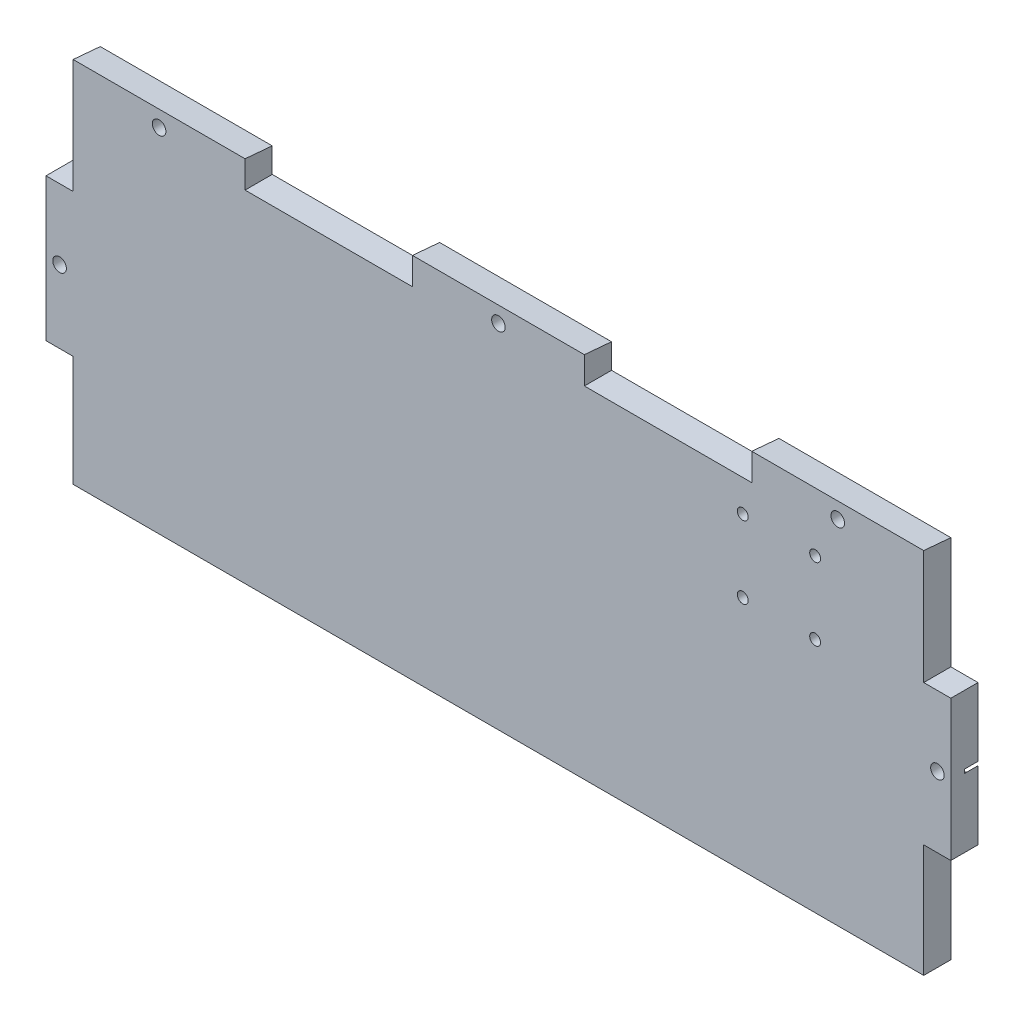
SolidWorks part; units mm, degrees
ref_plane "Plan de face" through (0, 0, 0) normal (0, 0, 1) x (1, 0, 0)
ref_plane "Plan de dessus" through (0, 0, 0) normal (0, 1, 0) x (1, 0, 0)
ref_plane "Plan de droite" through (0, 0, 0) normal (1, 0, 0) x (0, 0, -1)
sketch "Esquisse1" plane through (0, 0, 0) normal (0, 0, 1) x (1, 0, 0)
  line L1 (0, 0) -> (-188, 0)
  line L2 (0, 0) -> (0, 81.33)
  line L3 (0, 81.33) -> (-188, 81.33)
  line L4 (-188, 0) -> (-188, 81.33)
  dimension "D1" = 188
  dimension "D2" = 81.33
extrude "Boss.-Extru.1" add sketch "Esquisse1" along normal blind 6
sketch "Esquisse2" plane through (-188, 0, 0) normal (-1, 0, 0) x (0, 0, 1)
  line L0 (6, 81.33) -> (0, 80.8051)
  line L1 (0, 81.33) -> (0, 0) construction
  line L2 (6, 81.33) -> (6, 0) construction
  dimension "D1" = 85
extrude "Enlèv. mat.-Extru.2" cut sketch "Esquisse2" against normal through all and the other way through all flip side to cut contours L0
sketch "Esquisse4" plane through (-188, 0, 0) normal (-1, 0, 0) x (0, 0, 1)
  line L0 (6, 81.33) -> (6, 0) construction
  line L1 (6, 56.0675) -> (0, 56.0675)
  line L2 (6, 56.0675) -> (6, 24.5)
  line L3 (6, 24.5) -> (0, 24.5)
  line L4 (0, 56.0675) -> (0, 24.5)
  line L5 (0, 80.8051) -> (0, 0) construction
  line L6 (6, 81.33) -> (0, 80.8051) construction
  line L7 (6, 0) -> (0, 0) construction
  point P8 (3, 81.0675)
  point P11 (3, 0)
  dimension "D1" = 25
  dimension "D2" = 24.5
extrude "Boss.-Extru.2" add sketch "Esquisse4" along normal blind 6
sketch "Esquisse5" plane through (0, 0, 0) normal (1, 0, 0) x (0, 0, -1)
  line L0 (-6, 0) -> (-6, 81.33) construction
  line L1 (-6, 25) -> (0, 25)
  line L2 (-6, 25) -> (-6, 56.0675)
  line L3 (-6, 56.0675) -> (0, 56.0675)
  line L4 (0, 25) -> (0, 56.0675)
  line L5 (0, 0) -> (0, 80.8051) construction
  line L6 (-6, 0) -> (0, 0) construction
  line L7 (0, 80.8051) -> (-6, 81.33) construction
  point P10 (-3, 81.0675)
  dimension "D1" = 25
  dimension "D2" = 25
extrude "Boss.-Extru.3" add sketch "Esquisse5" along normal blind 6
sketch "Esquisse6" plane through (0, 0, 6) normal (0, 0, 1) x (1, 0, 0)
  line L0 (0, 81.33) -> (-188, 81.33) construction
  line L1 (-150, 81.33) -> (-113, 81.33)
  line L2 (-150, 81.33) -> (-150, 75.33)
  line L3 (-150, 75.33) -> (-113, 75.33)
  line L4 (-113, 81.33) -> (-113, 75.33)
  line L6 (-75, 81.33) -> (-38, 81.33)
  line L7 (-75, 81.33) -> (-75, 75.33)
  line L8 (-75, 75.33) -> (-38, 75.33)
  line L9 (-38, 81.33) -> (-38, 75.33)
  line L11 (0, 56.0675) -> (0, 81.33) construction
  dimension "D1" = 6
  dimension "D2" = 37
  dimension "D3" = 38
  dimension "D4" = 37
  dimension "D5" = 38
extrude "Enlèv. mat.-Extru.3" cut sketch "Esquisse6" against normal blind 6
sketch "Esquisse7" plane through (0, 0, 0) normal (0, 0, -1) x (-1, 0, 0)
  line L0 (113, 80.8051) -> (75, 80.8051) construction
  line L1 (113, 75.33) -> (113, 80.8051) construction
  line L2 (0, 56.0675) -> (0, 80.8051) construction
  line L3 (188, 80.8051) -> (188, 56.0675) construction
  line L4 (194, 56.0675) -> (194, 24.5) construction
  line L5 (194, 56.0675) -> (188, 56.0675) construction
  line L6 (-6, 56.0675) -> (0, 56.0675) construction
  circle A0 centre (94, 77.8051) radius 2.995
  circle A1 centre (19, 77.8051) radius 2.995
  circle A2 centre (169, 77.8051) radius 2.995
  circle A3 centre (191, 40.5675) radius 2.995
  circle A4 centre (-3.034, 40.5675) radius 2.995
  point P10 (113, 78.0675)
  point P23 (-3, 56.0675)
  dimension "D1" = 5.99
  dimension "D3" = 5.99
  dimension "D4" = 5.99
  dimension "D8" = 5.99
  dimension "D11" = 5.99
  dimension "D2" = 3
  dimension "D5" = 19
  dimension "D6" = 19
  dimension "D7" = 19
  dimension "D9" = 3
  dimension "D10" = 15.5
  dimension "D12" = 15.5
extrude "Enlèv. mat.-Extru.4" cut sketch "Esquisse7" against normal blind 3
sketch "Esquisse8" plane through (0, 0, 0) normal (0, 0, -1) x (-1, 0, 0)
  circle A0 centre (-3.034, 40.5675) radius 1.5
  circle A1 centre (19, 77.8051) radius 1.5
  circle A2 centre (94, 77.8051) radius 1.5
  circle A3 centre (169, 77.8051) radius 1.5
  circle A4 centre (191, 40.5675) radius 1.5
extrude "Enlèv. mat.-Extru.5" cut sketch "Esquisse8" against normal blind 6
sketch "Esquisse9" plane through (0, 0, 6) normal (0, 0, 1) x (1, 0, 0)
  line L0 (6, 56.0675) -> (6, 25) construction
  line L1 (0, 81.33) -> (-38, 81.33) construction
  circle A0 centre (-24, 68.33) radius 1.2
  circle A1 centre (-24, 52.33) radius 1.2
  circle A2 centre (-40, 68.33) radius 1.2
  circle A3 centre (-40, 52.33) radius 1.2
  dimension "D1" = 30
  dimension "D3" = 2.4
  dimension "D4" = 2.4
  dimension "D7" = 2.4
  dimension "D2" = 13
  dimension "D5" = 16
  dimension "D6" = 16
  dimension "D8" = 0
extrude "Enlèv. mat.-Extru.6" cut sketch "Esquisse9" against normal blind 10
